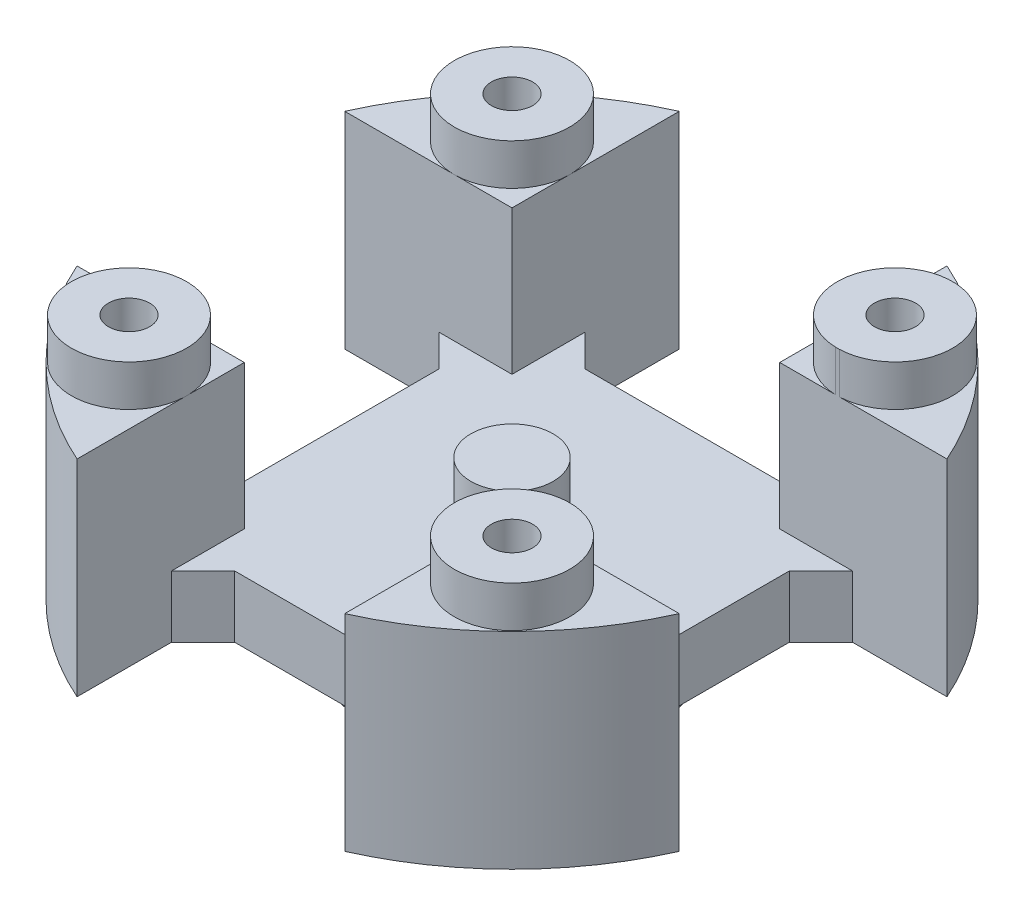
SolidWorks part; units mm, degrees
ref_plane "Alzado" through (0, 0, 0) normal (0, 0, 1) x (1, 0, 0)
ref_plane "Planta" through (0, 0, 0) normal (0, 1, 0) x (1, 0, 0)
ref_plane "Vista lateral" through (0, 0, 0) normal (1, 0, 0) x (0, 0, -1)
sketch "Croquis1" plane through (0, 0, 0) normal (0, 1, 0) x (1, 0, 0)
  circle A0 centre (0, 0) radius 16
  dimension "D1" = 32
extrude "Saliente-Extruir1" add sketch "Croquis1" along normal blind 10
sketch "Croquis2" plane through (0, 0, 0) normal (0, -1, 0) x (-1, 0, 0)
  line L0 (0, -16) -> (0, 16) construction
  line L1 (16, 0) -> (-16, 0) construction
  line L2 (8.5, -13.5554) -> (8.5, 13.5554) construction
  line L3 (-8.5, -13.5554) -> (-8.5, 13.5554) construction
  line L4 (13.5554, -8.5) -> (-13.5554, -8.5) construction
  line L5 (13.5554, 8.5) -> (-13.5554, 8.5) construction
  line L6 (0, 0) -> (-11.3137, -11.3137) construction
  line L7 (0, 0) -> (11.3137, 11.3137) construction
  line L8 (-12.9425, -9.407) -> (9.407, 12.9425) construction
  line L9 (-9.407, -12.9425) -> (12.9425, 9.407) construction
  line L10 (11.3137, -11.3137) -> (-11.3137, 11.3137) construction
  line L11 (9.407, -12.9425) -> (-12.9425, 9.407) construction
  line L12 (12.9425, -9.407) -> (-9.407, 12.9425) construction
  line L13 (14.6202, 6.5) -> (-14.6202, 6.5) construction
  line L14 (14.6202, -6.5) -> (-14.6202, -6.5) construction
  line L15 (6.5, -14.6202) -> (6.5, 14.6202) construction
  line L16 (-6.5, -14.6202) -> (-6.5, 14.6202) construction
  line L17 (14.6202, -6.5) -> (10.0355, -6.5)
  line L18 (10.0355, -6.5) -> (8.5, -4.9645)
  line L19 (8.5, -4.9645) -> (8.5, 4.9645)
  line L20 (8.5, 4.9645) -> (10.0355, 6.5)
  line L21 (10.0355, 6.5) -> (14.6202, 6.5)
  line L22 (-10.0355, 6.5) -> (-14.6202, 6.5)
  line L23 (-8.5, 4.9645) -> (-10.0355, 6.5)
  line L24 (-8.5, -4.9645) -> (-8.5, 4.9645)
  line L25 (-10.0355, -6.5) -> (-8.5, -4.9645)
  line L26 (-14.6202, -6.5) -> (-10.0355, -6.5)
  line L27 (6.5, -14.6202) -> (6.5, -10.0355)
  line L28 (6.5, -10.0355) -> (4.9645, -8.5)
  line L29 (4.9645, -8.5) -> (-4.9645, -8.5)
  line L30 (-4.9645, -8.5) -> (-6.5, -10.0355)
  line L31 (-6.5, -10.0355) -> (-6.5, -14.6202)
  line L32 (6.5, 14.6202) -> (6.5, 10.0355)
  line L33 (6.5, 10.0355) -> (4.9645, 8.5)
  line L34 (4.9645, 8.5) -> (-4.9645, 8.5)
  line L35 (-4.9645, 8.5) -> (-6.5, 10.0355)
  line L36 (-6.5, 10.0355) -> (-6.5, 14.6202)
  circle A0 centre (0, 0) radius 16 construction
  arc A1 (14.6202, -6.5) -> (16, 0) centre (0, 0) cw
  arc A2 (6.5, -14.6202) -> (0, -16) centre (0, 0) ccw
  arc A3 (6.5, 14.6202) -> (0, 16) centre (0, 0) cw
  dimension "D1" = 8.5
  dimension "D2" = 8.5
  dimension "D3" = 8.5
  dimension "D4" = 8.5
  dimension "D5" = 2.5
  dimension "D6" = 2.5
  dimension "D7" = 6.5
  dimension "D8" = 6.5
extrude "Cortar-Extruir2" cut sketch "Croquis2" against normal blind 10 contours L30 L31 L0 A1 L27 L28 L29 | L21 L20 L19 L18 L17 L0 | L0 L26 L25 L24 L23 L22 | L36 L35 L34 L33 L32 L0 A2
sketch "Croquis4" plane through (0, 0, 0) normal (0, -1, 0) x (1, 0, 0)
  line L0 (-8.5, 0) -> (8.5, 0) construction
  line L1 (-8.5, 4.9645) -> (-8.5, -4.9645) construction
  line L2 (8.5, 4.9645) -> (8.5, -4.9645) construction
  line L3 (-8.5, 6.5) -> (8.5, 6.5) construction
  line L4 (-19.3208, 0) -> (20.9643, 0) construction
  line L5 (20.9643, 0) -> (20.9643, 6.5) construction
  line L6 (20.9643, 6.5) -> (-19.3208, 6.5) construction
  line L7 (-19.3208, 6.5) -> (-19.3208, -6.5) construction
  line L8 (-19.3208, -6.5) -> (20.9643, -6.5) construction
  line L9 (20.9643, -6.5) -> (20.9643, 0) construction
  line L10 (0, 16.5994) -> (0, -17.2962) construction
  line L11 (0, -17.2962) -> (6.5, -17.2962) construction
  line L12 (6.5, -17.2962) -> (6.5, 16.5994) construction
  line L13 (6.5, 16.5994) -> (-6.5, 16.5994) construction
  line L14 (-6.5, 16.5994) -> (-6.5, -17.2962) construction
  line L15 (-6.5, -17.2962) -> (0, -17.2962) construction
  line L16 (-6.5, 16.5994) -> (-6.5, 6.5)
  line L17 (-6.5, 6.5) -> (-19.3208, 6.5)
  line L18 (-19.3208, 6.5) -> (-19.3208, -6.5)
  line L19 (-19.3208, -6.5) -> (-6.5, -6.5)
  line L20 (-6.5, -6.5) -> (-6.5, -17.2962)
  line L21 (-6.5, -17.2962) -> (6.5, -17.2962)
  line L22 (6.5, -17.2962) -> (6.5, -6.5)
  line L23 (6.5, -6.5) -> (20.9643, -6.5)
  line L24 (20.9643, -6.5) -> (20.9643, 6.5)
  line L25 (20.9643, 6.5) -> (6.5, 6.5)
  line L26 (6.5, 6.5) -> (6.5, 16.5994)
  line L27 (6.5, 16.5994) -> (-6.5, 16.5994)
  dimension "D1" = 6.5
extrude "Cortar-Extruir4" cut sketch "Croquis4" against normal blind 10 and the other way blind 7 from vertex at -10 starting at point (6.5, 10, 14.6202)
sketch "Croquis5" plane through (0, 3, 0) normal (0, 1, 0) x (1, 0, 0)
  circle A0 centre (0, 0) radius 2
extrude "Saliente-Extruir2" add sketch "Croquis5" along normal blind 3
sketch "Croquis6" plane through (0, 10, 0) normal (0, 1, 0) x (1, 0, 0)
  line L0 (-11.3137, 11.3137) -> (11.3137, -11.3137) construction
  line L1 (11.3137, 11.3137) -> (-11.3137, -11.3137) construction
  arc A1 (-6.5, 14.6202) -> (-14.6202, 6.5) centre (0, 0) ccw construction
  arc A2 (6.5, -14.6202) -> (14.6202, -6.5) centre (0, 0) ccw construction
  arc A3 (14.6202, 6.5) -> (6.5, 14.6202) centre (0, 0) ccw construction
  arc A4 (-14.6202, -6.5) -> (-6.5, -14.6202) centre (0, 0) ccw construction
  circle A5 centre (-9.2985, 9.2985) radius 2.8
  circle A6 centre (9.2985, -9.2985) radius 2.8
  circle A7 centre (-9.2985, -9.2985) radius 1
  circle A8 centre (-9.2985, -9.2985) radius 2.8
  circle A9 centre (-9.2985, 9.2985) radius 2.8
  circle A10 centre (9.2985, 9.2985) radius 2.8
  circle A11 centre (-9.2985, 9.2985) radius 1
  circle A12 centre (9.2985, 9.2985) radius 1
  circle A13 centre (9.2985, -9.2985) radius 1
  point P34 (0, 0)
  point P41 (0, 0)
  line M1 (6.5, 14.6202) -> (6.5, 6.5)
  line M2 (6.5, 6.5) -> (14.6202, 6.5)
  dimension "D2" = 4
  dimension "D3" = 4
extrude "Saliente-Extruir4" add sketch "Croquis6" along normal blind 2 contours A8 A7 | A5 A11 | A10 A12 M2 M1 | A6 A13
sketch "Croquis9" plane through (0, 10, 0) normal (0, 1, 0) x (1, 0, 0)
  circle A0 centre (-9.2985, 9.2985) radius 1
  circle A1 centre (9.2985, 9.2985) radius 1
  circle A2 centre (9.2985, -9.2985) radius 1
  circle A3 centre (-9.2985, -9.2985) radius 1
  point P12 (0, 0)
  dimension "D1" = 4
extrude "Cortar-Extruir5" cut sketch "Croquis9" against normal blind 12
sketch "Croquis10" plane through (0, 0, 0) normal (0, -1, 0) x (1, 0, 0)
  circle A0 centre (0, 0) radius 6.75
extrude "Saliente-Extruir5" add sketch "Croquis10" along normal blind 2
sketch "Croquis11" plane through (0, -2, 0) normal (0, -1, 0) x (1, 0, 0)
  circle A0 centre (0, 0) radius 6
extrude "Cortar-Extruir6" cut sketch "Croquis11" against normal blind 4
sketch "Croquis12" plane through (0, -2, 0) normal (0, -1, 0) x (1, 0, 0)
  circle A0 centre (0, 0) radius 0.375
extrude "Cortar-Extruir7" cut sketch "Croquis12" against normal blind 7
